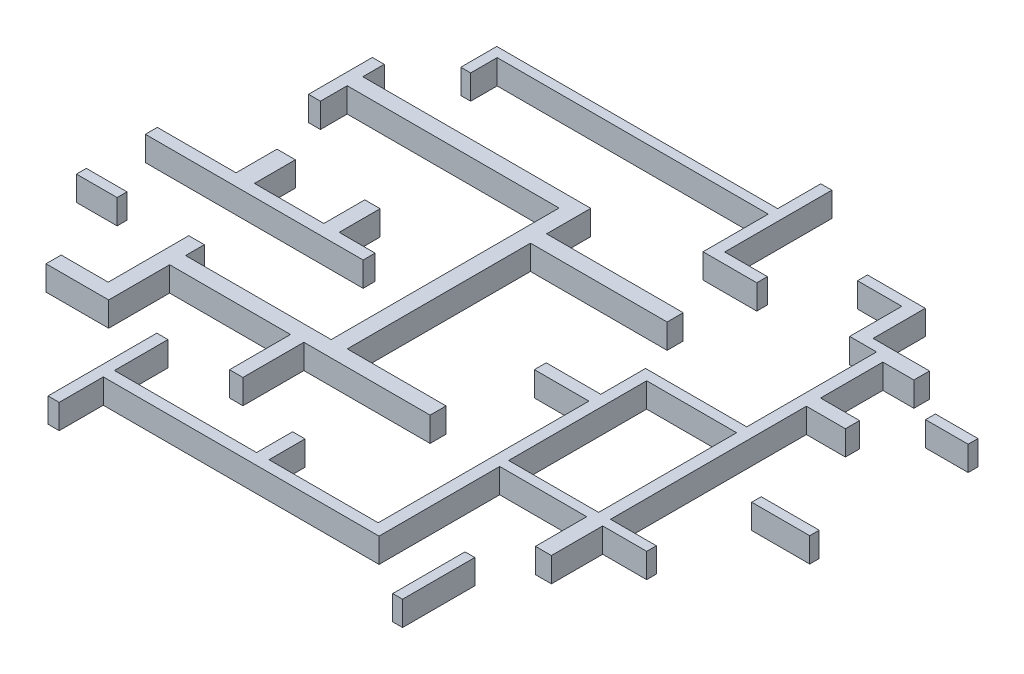
SolidWorks part; units mm, degrees
ref_plane "Front Plane" through (0, 0, 0) normal (0, 0, 1) x (1, 0, 0)
ref_plane "Top Plane" through (0, 0, 0) normal (0, 1, 0) x (1, 0, 0)
ref_plane "Right Plane" through (0, 0, 0) normal (1, 0, 0) x (0, 0, -1)
sketch "Sketch2" plane through (0, 0, 0) normal (0, 1, 0) x (1, 0, 0)
  line L0 (3.2579, 13.9505) -> (30.8579, 13.9505) construction
  line L1 (7.6055, 22.6025) -> (7.6055, 23.6815)
  line L2 (3.1468, 11.4121) -> (4.803, 11.4121)
  line L3 (3.1468, 11.4121) -> (3.1468, 11.0086)
  line L4 (3.1468, 11.0086) -> (4.803, 11.0086)
  line L5 (4.803, 11.4121) -> (4.803, 11.0086)
  line L6 (24.3785, 5.5979) -> (24.7783, 5.5979)
  line L7 (24.3785, 5.5979) -> (24.3785, 2.6558)
  line L8 (24.3785, 2.6558) -> (24.7783, 2.6558)
  line L9 (24.7783, 5.5979) -> (24.7783, 2.6558)
  line L10 (28.4657, 13.5733) -> (30.8285, 13.5733)
  line L11 (28.4657, 13.5733) -> (28.4657, 13.1861)
  line L12 (28.4657, 13.1861) -> (30.8285, 13.1861)
  line L13 (30.8285, 13.5733) -> (30.8285, 13.1861)
  line L14 (29.0944, 20.0377) -> (30.8285, 20.0377)
  line L15 (29.0944, 20.0377) -> (29.0944, 19.6371)
  line L16 (29.0944, 19.6371) -> (30.8285, 19.6371)
  line L17 (30.8285, 20.0377) -> (30.8285, 19.6371)
  line L18 (7.6055, 23.6815) -> (18.6428, 23.6815)
  line L19 (18.6428, 23.6815) -> (18.6428, 21.0268)
  line L20 (18.6428, 21.0268) -> (20.8309, 21.0268)
  line L21 (20.8309, 21.0268) -> (20.8309, 21.4612)
  line L22 (20.8309, 21.4612) -> (19.0933, 21.4612)
  line L23 (19.0933, 21.4612) -> (19.0933, 25.8214)
  line L24 (19.0933, 25.8214) -> (18.6428, 25.8214)
  line L25 (18.6428, 25.8214) -> (18.6428, 24.0677)
  line L26 (18.6428, 24.0677) -> (7.2032, 24.0677)
  line L27 (7.2032, 24.0677) -> (7.2032, 22.6025)
  line L28 (7.2032, 22.6025) -> (7.6055, 22.6025)
  line L29 (22.8095, 23.5575) -> (22.8095, 23.1504)
  line L30 (22.8095, 23.1504) -> (24.6135, 23.1504)
  line L31 (24.6135, 23.1504) -> (24.6135, 21.0268)
  line L32 (24.6135, 21.0268) -> (25.7085, 21.0268)
  line L33 (25.7085, 21.0268) -> (25.7085, 15.7415)
  line L34 (25.7085, 15.7415) -> (21.587, 15.7415)
  line L35 (21.587, 15.7415) -> (21.587, 13.9189)
  line L36 (21.587, 13.9189) -> (19.3649, 13.9189)
  line L37 (19.3649, 13.9189) -> (19.3649, 13.4362)
  line L38 (19.3649, 13.4362) -> (21.587, 13.4362)
  line L39 (21.587, 13.4362) -> (21.587, 4.8556)
  line L40 (21.587, 4.8556) -> (17.1397, 4.8556)
  line L41 (17.1397, 4.8556) -> (17.1397, 6.3228)
  line L42 (17.1397, 6.3228) -> (16.6341, 6.3228)
  line L43 (16.6341, 6.3228) -> (16.6341, 4.8556)
  line L44 (16.6341, 4.8556) -> (10.8459, 4.8556)
  line L45 (10.8459, 4.8556) -> (10.8459, 7.037)
  line L46 (10.8459, 7.037) -> (10.3918, 7.037)
  line L47 (10.3918, 7.037) -> (10.3918, 2.6078)
  line L48 (10.3918, 2.6078) -> (10.8459, 2.6078)
  line L49 (10.8459, 2.6078) -> (10.8459, 4.4032)
  line L50 (10.8459, 4.4032) -> (22.074, 4.4032)
  line L51 (22.074, 4.4032) -> (22.074, 9.3151)
  line L52 (22.074, 9.3151) -> (25.6182, 9.3151)
  line L53 (25.6182, 9.3151) -> (25.6182, 7.2264)
  line L54 (25.6182, 7.2264) -> (26.2678, 7.2264)
  line L55 (26.2678, 7.2264) -> (26.2678, 9.3151)
  line L56 (26.2678, 9.3151) -> (28.0605, 9.3151)
  line L57 (28.0605, 9.3151) -> (28.0605, 9.7091)
  line L58 (28.0605, 9.7091) -> (26.1938, 9.7091)
  line L59 (26.1938, 9.7091) -> (26.1938, 17.6838)
  line L60 (26.1938, 17.6838) -> (27.7833, 17.6838)
  line L61 (27.7833, 17.6838) -> (27.7833, 18.2601)
  line L62 (27.7833, 18.2601) -> (26.1938, 18.2601)
  line L63 (26.1938, 18.2601) -> (26.1938, 20.7974)
  line L64 (26.1938, 20.7974) -> (27.4578, 20.7974)
  line L65 (27.4578, 20.7974) -> (27.4578, 21.4343)
  line L66 (27.4578, 21.4343) -> (25.161, 21.4343)
  line L67 (25.161, 21.4343) -> (25.161, 23.5575)
  line L68 (25.161, 23.5575) -> (22.8095, 23.5575)
  line L69 (5.0577, 21.1467) -> (5.5437, 21.1467)
  line L70 (22.0454, 15.3285) -> (25.7085, 15.3285)
  line L71 (22.0454, 15.3285) -> (22.0454, 9.7091)
  line L72 (22.0454, 9.7091) -> (25.7085, 9.7091)
  line L73 (25.7085, 15.3285) -> (25.7085, 9.7091)
  line L74 (5.5437, 21.1467) -> (5.5437, 20.272)
  line L75 (5.5437, 20.272) -> (14.8257, 20.272)
  line L76 (14.8257, 20.272) -> (14.8257, 18.4739)
  line L77 (14.8257, 18.4739) -> (20.39, 18.4739)
  line L78 (20.39, 18.4739) -> (20.39, 17.8178)
  line L79 (20.39, 17.8178) -> (14.8257, 17.8178)
  line L80 (14.8257, 17.8178) -> (14.8257, 10.3582)
  line L81 (14.8257, 10.3582) -> (18.8471, 10.3582)
  line L82 (18.8471, 10.3582) -> (18.8471, 9.7091)
  line L83 (18.8471, 9.7091) -> (13.7079, 9.7091)
  line L84 (13.7079, 9.7091) -> (13.7079, 7.2264)
  line L85 (13.7079, 7.2264) -> (13.1612, 7.2264)
  line L86 (13.1612, 7.2264) -> (13.1612, 9.7091)
  line L87 (13.1612, 9.7091) -> (8.2408, 9.7091)
  line L88 (8.2408, 9.7091) -> (8.2408, 7.2264)
  line L89 (8.2408, 7.2264) -> (5.6895, 7.2264)
  line L90 (5.6895, 7.2264) -> (5.6895, 7.8434)
  line L91 (5.6895, 7.8434) -> (7.6055, 7.8434)
  line L92 (7.6055, 7.8434) -> (7.6055, 11.1236)
  line L93 (7.6055, 11.1236) -> (8.2408, 11.1236)
  line L94 (8.2408, 11.1236) -> (8.2408, 10.3582)
  line L95 (8.2408, 10.3582) -> (14.1696, 10.3582)
  line L96 (14.1696, 10.3582) -> (14.1696, 19.6371)
  line L97 (14.1696, 19.6371) -> (5.5437, 19.6371)
  line L98 (5.5437, 19.6371) -> (5.5437, 18.5468)
  line L99 (5.5437, 18.5468) -> (5.0577, 18.5468)
  line L100 (5.0577, 18.5468) -> (5.0577, 21.1467)
  line L101 (3.1468, 13.8152) -> (12.0138, 13.8152)
  line L102 (12.0138, 13.8152) -> (12.0138, 14.3032)
  line L103 (12.0138, 14.3032) -> (10.5498, 14.3032)
  line L104 (10.5498, 14.3032) -> (10.5498, 15.9715)
  line L105 (10.5498, 15.9715) -> (9.9256, 15.9715)
  line L106 (9.9256, 15.9715) -> (9.9256, 14.3032)
  line L107 (9.9256, 14.3032) -> (7.0997, 14.3032)
  line L108 (7.0997, 14.3032) -> (7.0997, 15.9715)
  line L109 (7.0997, 15.9715) -> (6.3506, 15.9715)
  line L110 (6.3506, 15.9715) -> (6.3506, 14.3032)
  line L111 (6.3506, 14.3032) -> (3.1468, 14.3032)
  line L112 (3.1468, 14.3032) -> (3.1468, 13.8152)
  point P110 (0, 0)
  dimension "D1" = 27.6
extrude "Boss-Extrude1" add sketch "Sketch2" along normal blind 1 contours L92 L93 L94 L95 L96 L97 L98 L99 L100 L69 L74 L75 L76 L77 L78 L79 L80 L81 L82 L83 L84 L85 L86 L87 L88 L89 L90 L91 | L39 L40 L41 L42 L43 L44 L45 L46 L47 L48 L49 L50 L51 L52 L53 L54 L55 L56 L57 L58 L59 L60 L61 L62 L63 L64 L65 L66 L67 L68 L29 L30 L31 L32 L33 L34 L35 L36 L37 L38 | L7 L8 L9 L6 | L10 L13 L12 L11 | L14 L17 L16 L15 | L104 L105 L106 L107 L108 L109 L110 L111 L112 L101 L102 L103 | L2 L5 L4 L3 | L23 L24 L25 L26 L27 L28 L1 L18 L19 L20 L21 L22 | L71 L70 L73 L72
sketch "Sketch4" plane through (0, 0, 0) normal (0, 1, 0) x (1, 0, 0)
  line L0 (21.1383, 20.3952) -> (21.1383, 26.4)
  line L1 (21.1383, 26.4) -> (6.6229, 26.4)
  line L2 (6.6229, 26.4) -> (6.6229, 21.9936)
  line L3 (6.6229, 21.9936) -> (18.0279, 21.9936)
  line L4 (18.0279, 21.9936) -> (18.0279, 20.3952)
  line L5 (18.0279, 20.3952) -> (21.1383, 20.3952)
  line L6 (22.3479, 24.0387) -> (22.3479, 16.3127)
  line L7 (22.3479, 16.3127) -> (18.9999, 16.3127)
  line L8 (18.9999, 16.3127) -> (18.9999, 11.8847)
  line L9 (18.9999, 11.8847) -> (21.1383, 11.8847)
  line L10 (21.1383, 11.8847) -> (21.1383, 6.0604)
  line L11 (21.1383, 6.0604) -> (17.6503, 6.0604)
  line L12 (17.6503, 6.0604) -> (17.6503, 7.0246)
  line L13 (17.6503, 7.0246) -> (15.5663, 7.0246)
  line L14 (15.5663, 7.0246) -> (15.5663, 5.5005)
  line L15 (15.5663, 5.5005) -> (11.5538, 5.5005)
  line L16 (11.5538, 5.5005) -> (11.5538, 7.74)
  line L17 (11.5538, 7.74) -> (9.5631, 7.74)
  line L18 (9.5631, 7.74) -> (9.5631, 2.3278)
  line L19 (9.5631, 2.3278) -> (11.896, 2.3278)
  line L20 (11.896, 2.3278) -> (11.896, 3.6031)
  line L21 (11.896, 3.6031) -> (22.3479, 3.6031)
  line L22 (22.3479, 3.6031) -> (22.3479, 8.9725)
  line L23 (22.3479, 8.9725) -> (25.0531, 8.9725)
  line L24 (25.0531, 8.9725) -> (25.0531, 7.0246)
  line L25 (25.0531, 7.0246) -> (27.0438, 7.0246)
  line L26 (27.0438, 7.0246) -> (27.0438, 8.7353)
  line L27 (27.0438, 8.7353) -> (28.4124, 8.7353)
  line L28 (28.4124, 8.7353) -> (28.4124, 10.1972)
  line L29 (28.4124, 10.1972) -> (26.515, 10.1972)
  line L30 (26.515, 10.1972) -> (26.515, 17.1024)
  line L31 (26.515, 17.1024) -> (28.4124, 17.1024)
  line L32 (28.4124, 17.1024) -> (28.4124, 18.7198)
  line L33 (28.4124, 18.7198) -> (26.515, 18.7198)
  line L34 (26.515, 18.7198) -> (26.515, 20.3373)
  line L35 (26.515, 20.3373) -> (27.7281, 20.3373)
  line L36 (27.7281, 20.3373) -> (27.7281, 21.8303)
  line L37 (27.7281, 21.8303) -> (25.6752, 21.8303)
  line L38 (25.6752, 21.8303) -> (25.6752, 24.0387)
  line L39 (25.6752, 24.0387) -> (22.3479, 24.0387)
  line L40 (28.8601, 20.3373) -> (30.9894, 20.3373)
  line L41 (30.9894, 20.3373) -> (30.9894, 19.3)
  line L42 (30.9894, 19.3) -> (28.8601, 19.3)
  line L43 (28.8601, 19.3) -> (28.8601, 20.3373)
  line L44 (28.0858, 13.9768) -> (30.9894, 13.9768)
  line L45 (30.9894, 13.9768) -> (30.9894, 12.9444)
  line L46 (30.9894, 12.9444) -> (28.0858, 12.9444)
  line L47 (28.0858, 12.9444) -> (28.0858, 13.9768)
  line L48 (23.9885, 6.0604) -> (25.0531, 6.0604)
  line L49 (25.0531, 6.0604) -> (25.0531, 2.3278)
  line L50 (25.0531, 2.3278) -> (23.9885, 2.3278)
  line L51 (23.9885, 2.3278) -> (23.9885, 6.0604)
  line L52 (5.3733, 6.9114) -> (8.7286, 6.9114)
  line L53 (8.7286, 6.9114) -> (8.7286, 8.9725)
  line L54 (8.7286, 8.9725) -> (12.6968, 8.9725)
  line L55 (12.6968, 8.9725) -> (12.6968, 6.9114)
  line L56 (12.6968, 6.9114) -> (14.4712, 6.9114)
  line L57 (14.4712, 6.9114) -> (14.4712, 9.2343)
  line L58 (14.4712, 9.2343) -> (19.3105, 9.2343)
  line L59 (19.3105, 9.2343) -> (19.3105, 11.0732)
  line L60 (19.3105, 11.0732) -> (15.2778, 11.0732)
  line L61 (15.2778, 11.0732) -> (15.2778, 17.1024)
  line L62 (15.2778, 17.1024) -> (20.7623, 17.1024)
  line L63 (20.7623, 17.1024) -> (20.7623, 18.7198)
  line L64 (20.7623, 18.7198) -> (15.2778, 18.7198)
  line L65 (15.2778, 18.7198) -> (15.2778, 20.6873)
  line L66 (15.2778, 20.6873) -> (6.2121, 20.6873)
  line L67 (6.2121, 20.6873) -> (6.2121, 21.3648)
  line L68 (6.2121, 21.3648) -> (4.2764, 21.3648)
  line L69 (4.2764, 21.3648) -> (4.2764, 17.9111)
  line L70 (4.2764, 17.9111) -> (13.084, 17.9111)
  line L71 (13.084, 17.9111) -> (13.084, 11.4603)
  line L72 (13.084, 11.4603) -> (6.6229, 11.4603)
  line L73 (6.6229, 11.4603) -> (6.6229, 8.7353)
  line L74 (6.6229, 8.7353) -> (5.3733, 8.7353)
  line L75 (5.3733, 8.7353) -> (5.3733, 6.9114)
  line L76 (2.9214, 10.6861) -> (5.0184, 10.6861)
  line L77 (5.0184, 10.6861) -> (5.0184, 11.8847)
  line L78 (5.0184, 11.8847) -> (2.9214, 11.8847)
  line L79 (2.9214, 11.8847) -> (2.9214, 10.6861)
split "Split1" trim tools "Sketch4" bodies to split 101 108 102 105 104 103 107 106 resulting bodies 109 110 111 112 113 114 115 116
